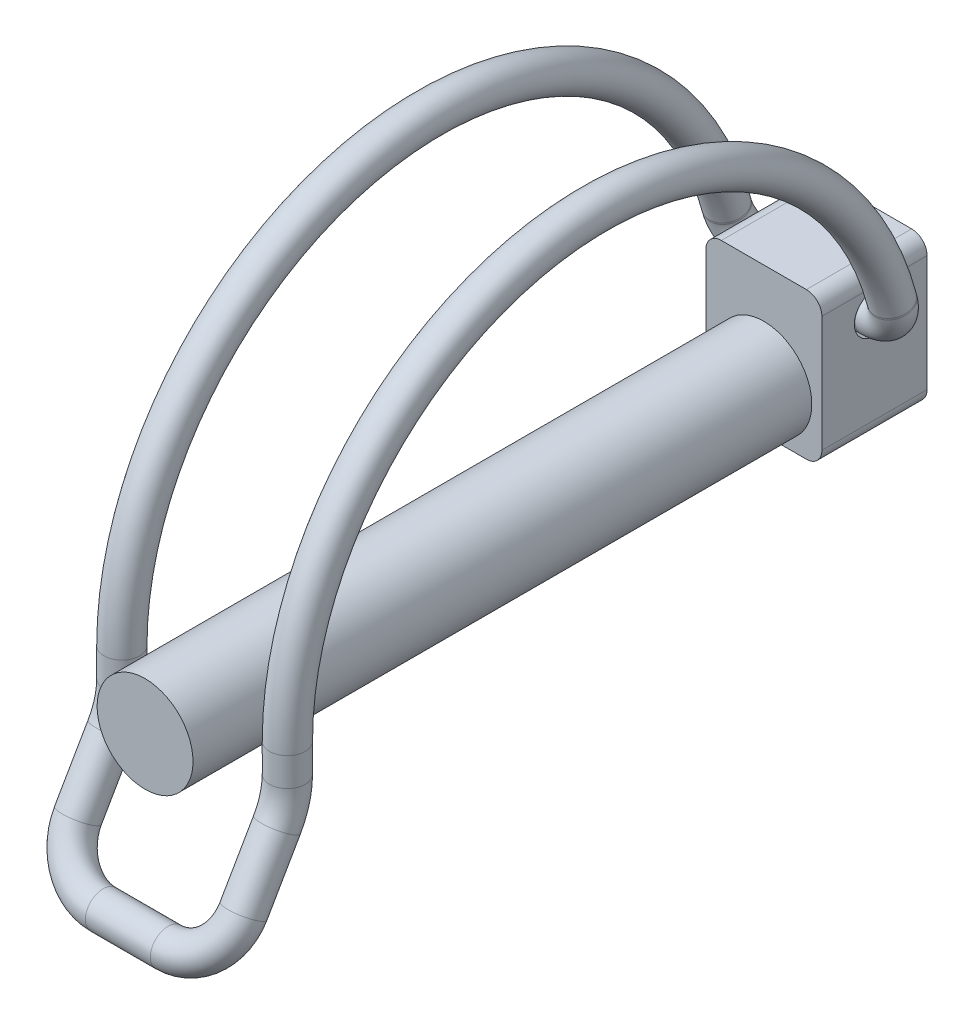
SolidWorks part; units mm, degrees
ref_plane "Front" through (0, 0, 0) normal (0, 0, 1) x (1, 0, 0)
ref_plane "Top" through (0, 0, 0) normal (0, 1, 0) x (1, 0, 0)
ref_plane "Right" through (0, 0, 0) normal (1, 0, 0) x (0, 0, -1)
sketch "Sketch1" plane through (0, 0, 0) normal (0, 0, 1) x (1, 0, 0)
  circle A0 centre (0, 0) radius 3.937
  dimension "D1" = 7.874
extrude "Boss-Extrude1" add sketch "Sketch1" along normal blind 50.8
sketch "Sketch2" plane through (0, 0, 0) normal (0, 0, -1) x (-1, 0, 0)
  line L0 (0, 0) -> (0, 1.905) construction
  line L1 (-3.4925, 7.9375) -> (3.4925, 7.9375)
  line L2 (-4.7625, 6.6675) -> (-4.7625, -2.8575)
  line L3 (-3.4925, -4.1275) -> (3.4925, -4.1275)
  line L4 (4.7625, 6.6675) -> (4.7625, -2.8575)
  line L5 (-4.7625, 7.9375) -> (4.7625, -4.1275) construction
  line L6 (-4.7625, -4.1275) -> (4.7625, 7.9375) construction
  arc A1 (-4.7625, -2.8575) -> (-3.4925, -4.1275) centre (-3.4925, -2.8575) ccw
  arc A2 (3.4925, -4.1275) -> (4.7625, -2.8575) centre (3.4925, -2.8575) ccw
  arc A3 (3.4925, 7.9375) -> (4.7625, 6.6675) centre (3.4925, 6.6675) cw
  arc A4 (-3.4925, 7.9375) -> (-4.7625, 6.6675) centre (-3.4925, 6.6675) ccw
  point P0 (0, 1.905)
  dimension "D3" = 1.27
  dimension "D1" = 9.525
  dimension "D2" = 12.065
  dimension "D4" = 1.905
extrude "Boss-Extrude2" add sketch "Sketch2" along normal blind 8.636
sketch "Sketch3" plane through (0, 0, 0) normal (1, 0, 0) x (0, 0, -1)
  line L0 (4.318, 7.9375) -> (4.318, 4.7625) construction
  line L1 (8.636, 7.9375) -> (0, 7.9375) construction
  line L2 (4.318, 4.7625) -> (3.8907, 6.3572) construction
  circle A0 centre (4.318, 4.7625) radius 1.651
  dimension "D2" = 3.302
  dimension "D1" = 3.175
  dimension "D3" = 15
extrude "Cut-Extrude1" cut sketch "Sketch3" against normal through all and the other way through all
ref_plane "Plane1" through (0, 1.3985, -5.2194) normal (0, -0.2588, 0.9659) x (1, 0, 0)
sketch "Sketch4" plane through (0, 1.3985, -5.2194) normal (0, -0.2588, 0.9659) x (1, 0, 0)
  line L0 (0, 0) -> (0, 3.4826) construction
  line L1 (-4.6355, 3.4826) -> (4.6355, 3.4826)
  line L2 (-6.7945, 5.6416) -> (-6.7945, 5.7686)
  line L3 (6.7945, 5.6416) -> (6.7945, 5.7686)
  line L4 (8.255, 5.7686) -> (5.334, 5.7686) construction
  line L5 (-5.334, 5.7686) -> (-8.255, 5.7686) construction
  arc A0 (4.6355, 3.4826) -> (6.7945, 5.6416) centre (4.6355, 5.6416) ccw
  arc A1 (-4.6355, 3.4826) -> (-6.7945, 5.6416) centre (-4.6355, 5.6416) cw
  dimension "D1" = 2.159
  dimension "D2" = 0.127
  dimension "D4" = 2.921
  dimension "D3" = 16.51
ref_plane "Plane2" through (-6.7945, 0, 0) normal (1, 0, 0) x (0, 0, -1)
sketch "Sketch5" plane through (-6.7945, 0, 0) normal (1, 0, 0) x (0, 0, -1)
  line L0 (3.7592, 6.8479) -> (3.7263, 6.9706) construction
  line L1 (-20.6619, 0.4358) -> (0, 0.4358) construction
  line L2 (-20.6619, 25.6844) -> (-20.6619, 0.4358) construction
  line L3 (-47.371, 0.4358) -> (-44.45, 0.4358) construction
  line L4 (-45.9105, 0.4358) -> (-45.9105, -1.905)
  line L5 (-46.7612, -5.08) -> (-49.5109, -9.8425)
  line L6 (-45.9105, -1.905) -> (-45.9105, -9.8425) construction
  line L7 (-45.9105, -9.8425) -> (-49.5109, -9.8425) construction
  line L8 (0, -1.905) -> (0, 1.905) construction
  line L10 (3.7592, 6.8479) -> (3.7263, 6.9706) construction
  line L11 (-20.6619, 27.1449) -> (-20.6619, 24.2239) construction
  line L13 (0, 3.937) -> (0, -3.937) construction
  line L14 (0, -2.8575) -> (0, -4.1275) construction
  line L15 (0, 6.6675) -> (0, -2.8575) construction
  line L16 (0, -1.905) -> (-45.9105, -1.905) construction
  arc A0 (3.7263, 6.9706) -> (-45.9105, 0.4358) centre (-20.6619, 0.4358) ccw
  arc A1 (-45.9105, -1.905) -> (-46.7612, -5.08) centre (-52.2605, -1.905) cw
  dimension "D2" = 6.35
  dimension "D3" = 30
  dimension "D4" = 7.9375
  dimension "D5" = 2.921
  dimension "D1" = 44.45
ref_plane "Plane3" through (6.7945, 0, 0) normal (1, 0, 0) x (0, 0, -1)
sketch "Sketch6" plane through (6.7945, 0, 0) normal (1, 0, 0) x (0, 0, -1)
  line L0 (-46.7612, -5.08) -> (-49.5109, -9.8425) construction
  line L1 (-45.9105, 0.4358) -> (-45.9105, -1.905) construction
  line L2 (-46.7612, -5.08) -> (-49.5109, -9.8425)
  line L3 (-45.9105, 0.4358) -> (-45.9105, -1.905)
  arc A0 (-46.7612, -5.08) -> (-45.9105, -1.905) centre (-52.2605, -1.905) ccw construction
  arc A1 (3.7263, 6.9706) -> (-45.9105, 0.4358) centre (-20.6619, 0.4358) ccw construction
  arc A2 (-46.7612, -5.08) -> (-45.9105, -1.905) centre (-52.2605, -1.905) ccw
  arc A3 (3.7263, 6.9706) -> (-45.9105, 0.4358) centre (-20.6619, 0.4358) ccw
ref_plane "Plane4" through (0, 18.9782, 32.8712) normal (0, -0.5, -0.866) x (-1, 0, 0)
sketch "Sketch7" plane through (0, 18.9782, 32.8712) normal (0, -0.5, -0.866) x (-1, 0, 0)
  line L0 (-6.7945, -33.2793) -> (6.7945, -33.2793) construction
  line L1 (-6.7945, -27.78) -> (-6.7945, -33.2793) construction
  line L2 (6.7945, -27.78) -> (6.7945, -33.2793) construction
  line L3 (-2.667, -37.4068) -> (2.667, -37.4068)
  arc A0 (-6.7945, -33.2793) -> (-2.667, -37.4068) centre (-2.667, -33.2793) ccw
  arc A1 (2.667, -37.4068) -> (6.7945, -33.2793) centre (2.667, -33.2793) ccw
  dimension "D1" = 4.1275
curve "CompCurve1"
sketch "Sketch8" plane through (0, 0, 0) normal (1, 0, 0) x (0, 0, -1)
  circle A0 centre (4.318, 4.7625) radius 1.4605
  dimension "D1" = 2.921
sweep "Sweep1" add profiles "Sketch8" path "CompCurve1"
equation "\"D1@Sketch7\"=\"D3@Sketch4\"*.25"
equation "\"D5@Sketch5\"=\"D4@Sketch4\""
